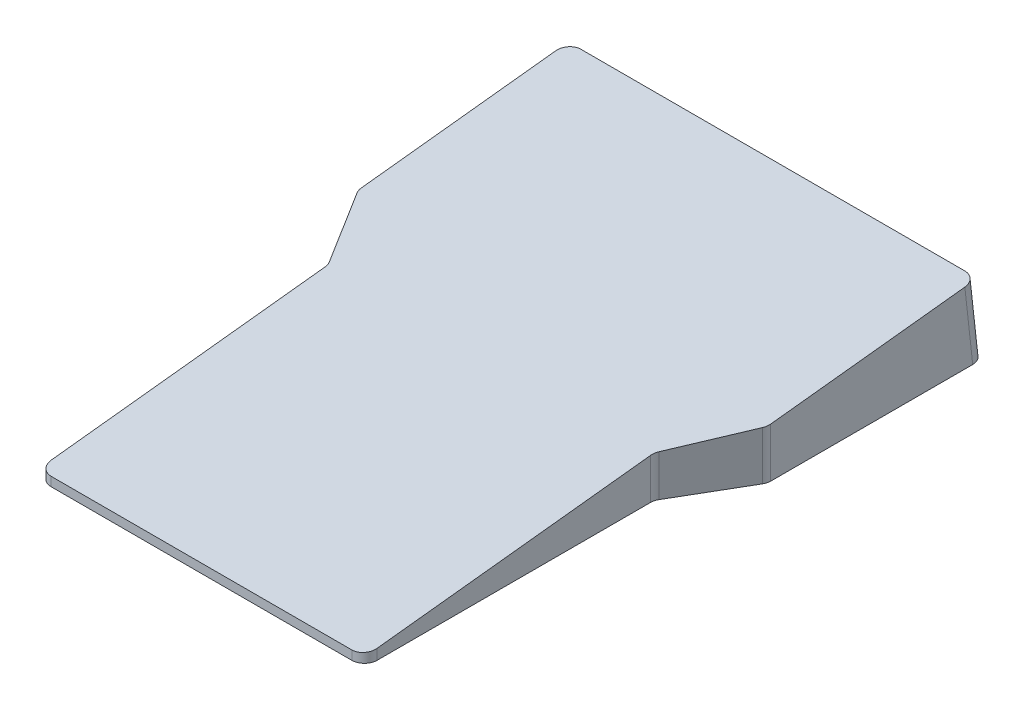
SolidWorks part; units mm, degrees
ref_plane "Front Plane" through (0, 0, 0) normal (0, 0, 1) x (1, 0, 0)
ref_plane "Top Plane" through (0, 0, 0) normal (0, 1, 0) x (1, 0, 0)
ref_plane "Right Plane" through (0, 0, 0) normal (1, 0, 0) x (0, 0, -1)
sketch "Sketch1" plane through (0, 0, 0) normal (0, 1, 0) x (1, 0, 0)
  line L0 (-57.5973, -8.4441) -> (-46.0973, -28.1941)
  line L1 (-46.0973, 51.8059) -> (43.9027, 51.8059)
  line L2 (-46.0973, 51.8059) -> (-46.0973, -108.1941)
  line L3 (-46.0973, -108.1941) -> (43.9027, -108.1941)
  line L4 (43.9027, 51.8059) -> (43.9027, -108.1941)
  line L5 (-57.5973, 51.8059) -> (55.4027, 51.8059)
  line L6 (-57.5973, 51.8059) -> (-57.5973, -8.4441)
  line L7 (-57.5973, -8.4441) -> (55.4027, -8.4441)
  line L8 (55.4027, 51.8059) -> (55.4027, -8.4441)
  line L9 (-57.5973, -8.4441) -> (-46.0973, -8.4441)
  line L10 (-46.0973, -8.4441) -> (-46.0973, -28.1941)
  line L11 (43.9027, -28.1941) -> (43.9027, -8.4441)
  line L12 (43.9027, -8.4441) -> (55.4027, -8.4441)
  line L13 (43.9027, -28.1941) -> (55.4027, -8.4441)
  point P12 (-1.0973, 51.8059)
  point P13 (-1.0973, 51.8059)
  dimension "D1" = 90
  dimension "D2" = 160
  dimension "D3" = 99.75
  dimension "D4" = 113
extrude "Boss-Extrude1" add sketch "Sketch1" along normal blind 20 contours L8 L5 L4 L7 | L2 L7 L4 L1 | L6 L7 L2 L5 | L7 L0 L2 | L7 L2 L3 L4 | L4 L13 L7
sketch "Sketch2" plane through (0, 0, 0) normal (0, -1, 0) x (1, 0, 0)
  line L2 (-46.0973, 28.1941) -> (-46.0973, 108.1941) construction
  line L3 (-57.5973, -51.8059) -> (55.4027, -51.8059) construction
  line L4 (-57.5973, -51.8059) -> (-57.5973, 8.4441) construction
  line L5 (55.4027, -51.8059) -> (55.4027, 8.4441) construction
  circle A2 centre (-51.0973, -45.3059) radius 2.4
  circle A3 centre (48.9027, -45.3059) radius 2.4
  circle A4 centre (-31.8473, -5.1309) radius 2.4
  circle A5 centre (-21.8473, -5.1309) radius 2.4
  circle A6 centre (47.4027, 6.9441) radius 2.35
  circle A7 centre (-49.5973, 6.9441) radius 2.35
  dimension "D5" = 4.8
  dimension "D6" = 4.8
  dimension "D12" = 4.8
  dimension "D13" = 4.8
  dimension "D16" = 21.25
  dimension "D18" = 4.7
  dimension "D19" = 4.7
  dimension "D2" = 8
  dimension "D3" = 21.25
  dimension "D4" = 8
  dimension "D7" = 6.5
  dimension "D8" = 6.5
  dimension "D9" = 6.5
  dimension "D10" = 6.5
  dimension "D11" = 10
  dimension "D14" = 14.25
  dimension "D15" = 46.675
extrude "Boss-Extrude2" add sketch "Sketch2" along normal blind 3
sketch "Sketch3" plane through (55.4027, 0, 0) normal (1, 0, 0) x (0, 0, -1)
  line L0 (-108.1941, 0) -> (-108.1941, 2.5)
  line L1 (-108.1941, 20) -> (-108.1941, 0) construction
  line L2 (-108.1941, 2.5) -> (49.5876, 20)
  line L3 (51.8059, 20) -> (-8.4441, 20) construction
  line L4 (49.5876, 20) -> (51.8059, 0)
  line L5 (51.8059, 0) -> (-108.1941, 0)
  line L6 (-108.1941, 20) -> (-108.1941, 2.5)
  line L7 (51.8059, 0) -> (51.8059, 20)
  line L8 (51.8059, 20) -> (49.5876, 20)
  line L9 (49.5876, 20) -> (-108.1941, 20)
  line M5 (51.8059, 0) -> (51.8059, 20)
  line M6 (51.8059, 20) -> (-8.4441, 20)
  line M7 (-8.4441, 20) -> (-8.4441, 0)
  dimension "D1" = 2.5
  dimension "D2" = 90
extrude "Cut-Extrude1" cut sketch "Sketch3" against normal through all contours L9 L6 L2 M7 | L2 M7 M6 | L4 M6 M5
fillet "Fillet1" radius 3.5 8 edges at (55.4027, 10, -50.6967) (-57.5973, 10, -50.6967) (-57.5973, 6.7818, 8.4441) (-46.0973, 5.6865, 28.1941) (-46.0973, 1.25, 108.1941) (43.9027, 1.25, 108.1941) (43.9027, 5.6865, 28.1941) (55.4027, 6.7818, 8.4441)
